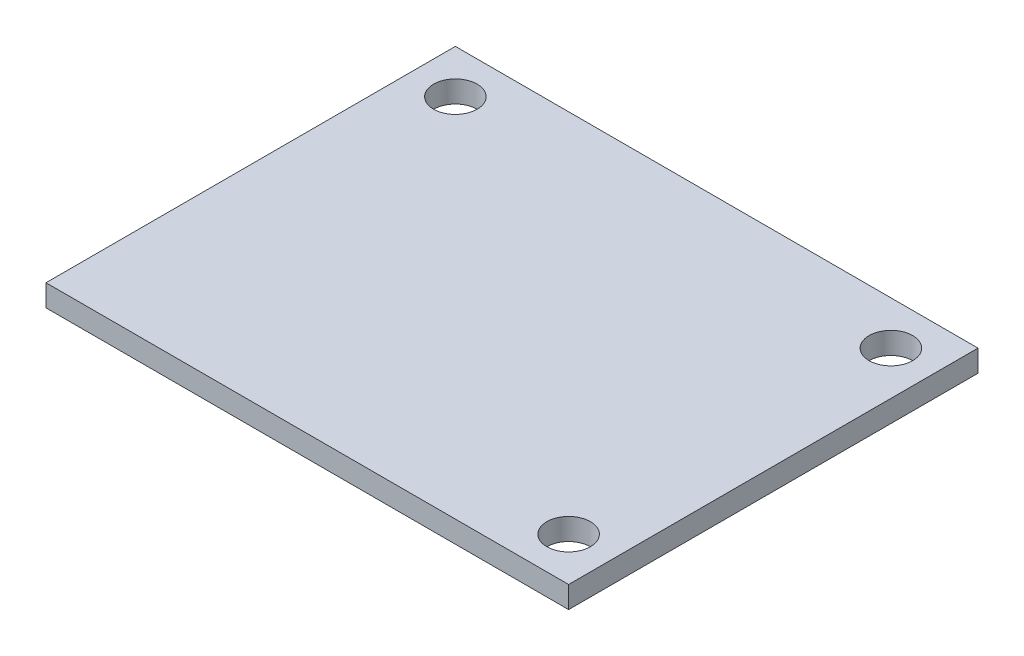
SolidWorks part; units mm, degrees
ref_plane "Front Plane" through (0, 0, 0) normal (0, 0, 1) x (1, 0, 0)
ref_plane "Top Plane" through (0, 0, 0) normal (0, 1, 0) x (1, 0, 0)
ref_plane "Right Plane" through (0, 0, 0) normal (1, 0, 0) x (0, 0, -1)
sketch "Sketch1" plane through (0, 0, 0) normal (0, 1, 0) x (1, 0, 0)
  line L1 (-19.05, -14.9225) -> (19.05, -14.9225)
  line L2 (-19.05, -14.9225) -> (-19.05, 14.9225)
  line L3 (-19.05, 14.9225) -> (19.05, 14.9225)
  line L4 (19.05, -14.9225) -> (19.05, 14.9225)
  line L5 (-19.05, -14.9225) -> (19.05, 14.9225) construction
  line L6 (-19.05, 14.9225) -> (19.05, -14.9225) construction
  point P0 (0, 0)
  dimension "D1" = 38.1
  dimension "D2" = 29.845
extrude "Boss-Extrude1" add sketch "Sketch1" along normal blind 1.5875
sketch "Sketch2" plane through (0, 1.5875, 0) normal (0, 1, 0) x (1, 0, 0)
  line L1 (-15.875, -11.7475) -> (15.875, -11.7475) construction
  line L2 (-15.875, -11.7475) -> (-15.875, 11.7475) construction
  line L3 (-15.875, 11.7475) -> (15.875, 11.7475) construction
  line L4 (15.875, -11.7475) -> (15.875, 11.7475) construction
  line L5 (-15.875, -11.7475) -> (15.875, 11.7475) construction
  line L6 (-15.875, 11.7475) -> (15.875, -11.7475) construction
  circle A0 centre (-15.875, 11.7475) radius 1.5875
  circle A1 centre (15.875, 11.7475) radius 1.5875
  circle A2 centre (15.875, -11.7475) radius 1.5875
  point P0 (0, 0)
  dimension "D3" = 3.175
  dimension "D1" = 31.75
  dimension "D2" = 23.495
extrude "Cut-Extrude1" cut sketch "Sketch2" against normal through all
